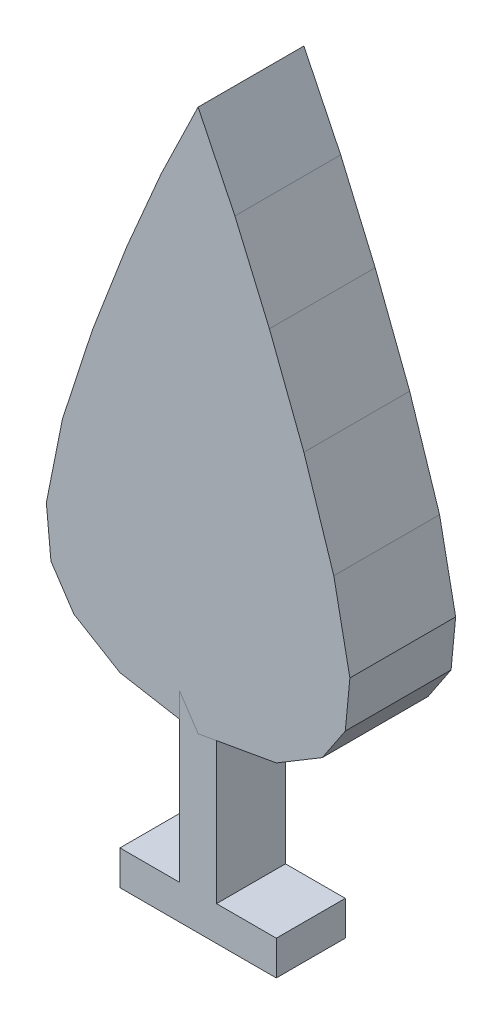
SolidWorks part; units mm, degrees
ref_plane "前视基准面" through (0, 0, 0) normal (0, 0, 1) x (1, 0, 0)
ref_plane "上视基准面" through (0, 0, 0) normal (0, 1, 0) x (1, 0, 0)
ref_plane "右视基准面" through (0, 0, 0) normal (1, 0, 0) x (0, 0, -1)
other "Configuration Table"
sketch "草图2" plane through (0, 0, 0) normal (0, 0, 1) x (1, 0, 0)
  line L1 (-8, -91) -> (8, -91)
  line L2 (-8, -91) -> (-8, 1)
  line L3 (-8, 1) -> (8, 1)
  line L4 (8, -91) -> (8, 1)
  line L5 (-8, -91) -> (8, 1) construction
  line L6 (-8, 1) -> (8, -91) construction
  point P0 (0, -45)
extrude "凸台-拉伸2" add sketch "草图2" against normal blind 30 separate body
sketch "草图3" plane through (0, 0, 0) normal (0, 0, 1) x (1, 0, 0)
  line L0 (0, 205) -> (16, 172)
  line L1 (16, 172) -> (31, 137)
  line L2 (31, 137) -> (46, 98)
  line L3 (46, 98) -> (59, 58)
  line L4 (59, 58) -> (66, 23)
  line L5 (66, 23) -> (64, 2)
  line L6 (64, 2) -> (54, -13)
  line L7 (54, -13) -> (34, -25)
  line L8 (34, -25) -> (0, -31)
  line L9 (0, -31) -> (-34, -25)
  line L10 (-34, -25) -> (-54, -13)
  line L11 (-54, -13) -> (-64, 2)
  line L12 (-64, 2) -> (-66, 23)
  line L13 (-66, 23) -> (-59, 58)
  line L14 (-59, 58) -> (-46, 98)
  line L15 (-46, 98) -> (-31, 137)
  line L16 (-31, 137) -> (-16, 172)
  line L17 (-16, 172) -> (0, 205)
extrude "凸台-拉伸3" add sketch "草图3" against normal blind 46 separate body
sketch "草图4" plane through (0, -91, 0) normal (0, -1, 0) x (1, 0, 0)
  line L0 (-34, 0) -> (34, 0)
  line L1 (34, 0) -> (34, -30)
  line L2 (34, -46) -> (34, 0) construction
  line L3 (34, -30) -> (-34, -30)
  line L4 (-34, -46) -> (-34, 0) construction
  line L5 (-34, -30) -> (-34, 0)
extrude "凸台-拉伸4" add sketch "草图4" along normal blind 15
